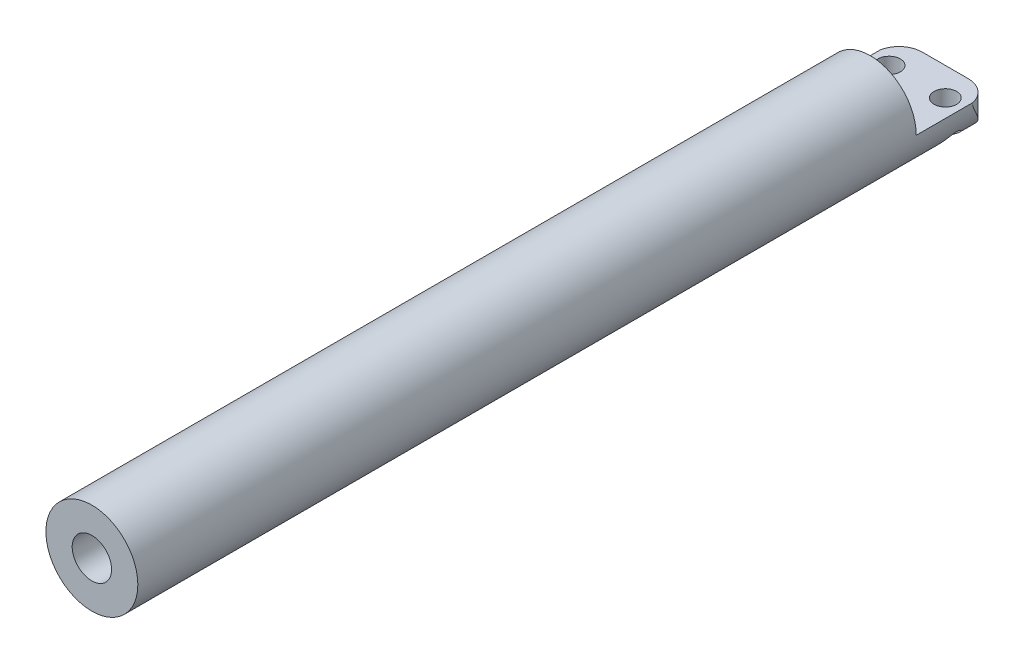
SolidWorks part; units mm, degrees
material "7050-T73510"
ref_plane "Plano frontal" through (0, 0, 0) normal (0, 0, 1) x (1, 0, 0)
ref_plane "Plano superior" through (0, 0, 0) normal (0, 1, 0) x (1, 0, 0)
ref_plane "Plano direito" through (0, 0, 0) normal (1, 0, 0) x (0, 0, -1)
sketch "Esboço1" plane through (0, 0, 0) normal (0, 0, 1) x (1, 0, 0)
  circle A0 centre (0, 0) radius 4.9
  dimension "D1" = 9.8
extrude "Ressalto-extrusão1" add sketch "Esboço1" along normal blind 91
sketch "Esboço10" plane through (0, 0, 0) normal (0, 0, -1) x (-1, 0, 0)
  line L0 (-5, 0) -> (5, 0)
  arc A0 (5, 0) -> (-5, 0) centre (0, 0) ccw
  dimension "D1" = 10
hole_wizard "Furo roscado de M51" positions "3DSketch6" profile "Esboço11" tap size "M5" standard "ISO"
sketch3d "3DSketch6"
  line L0 (0, 0, 91) -> (0, 0, 0) construction
  point P0 (0, 0, 91)
cosmetic thread "Rosca de furo1" parameters "D1"=10, "D2"=5
sketch "Esboço11" plane through (0, 0, 91) normal (1, 0, 0) x (0, -1, 0)
  line L0 (0, 0) -> (0, 14)
  line L1 (0, 14) -> (2.1, 12.7382)
  line L2 (2.1, 12.7382) -> (2.1, 0)
  line L5 (2.1, 0) -> (0, 0)
  line L10 (0, 14) -> (-2.1, 12.7382) construction
  line L11 (0, -6.35) -> (0, 107.95) construction
  dimension "Tap Drill Dia." = 4.2
  dimension "Tap Drill Depth" = 14
  dimension "Drill Angle" = 118
sketch "Esboço12" plane through (0, 0, 91) normal (0, 0, 1) x (1, 0, 0)
  point P0 (0, 0)
sketch "Esboço16" plane through (0, 0, 91) normal (0, 0, 1) x (1, 0, 0)
  circle A0 centre (0, 0) radius 5.1
  circle A1 centre (0, 0) radius 4.9
  circle A2 centre (0, 0) radius 4.9 construction
  dimension "D1" = 10.2
extrude "Corte-extrusão1" cut sketch "Esboço10" against normal blind 8
sketch "Esboço18" plane through (0, 0, 0) normal (0, 1, 0) x (1, 0, 0)
  line L0 (-4.9, 0) -> (0, -5) construction
  line L1 (0, -5) -> (0, 0) construction
  line L2 (0, 0) -> (-4.9, 0) construction
  line L3 (4.9, 0) -> (0, -5) construction
  line L4 (-4.9, -8) -> (-4.9, 0) construction
  line L5 (4.9, 0) -> (-4.9, 0) construction
  line L7 (-4.9, -2.0025) -> (-4.9, 0)
  line L8 (-4.9, 0) -> (-2.45, 0)
  line L9 (2.45, 0) -> (4.9, 0)
  line L10 (4.9, 0) -> (4.9, -2.0025)
  line L12 (-4.9, 0) -> (4.9, 0) construction
  line L14 (4.9, 0) -> (4.9, -8) construction
  arc A0 (-4.9, -2.0025) -> (-2.45, 0) centre (-2.45, -2.5) cw
  arc A1 (2.45, 0) -> (4.9, -2.0025) centre (2.45, -2.5) cw
  point P12 (4.4506, -0.8738)
  point P13 (2.3093, 0)
  point P23 (4.8, -1.8)
  dimension "D2" = 2.5
  dimension "D3" = 2.5
  dimension "D1" = 5
extrude "Corte-extrusão2" cut sketch "Esboço18" against normal through all
sketch "Esboço19" plane through (0, 0, 0) normal (0, 1, 0) x (1, 0, 0)
  line L0 (0, 0) -> (0, -3) construction
  line L1 (2.45, 0) -> (-2.45, 0) construction
  line L2 (-3, -3) -> (3, -3)
  point P7 (0, -3)
  dimension "D1" = 6
  dimension "D2" = 3
hole_wizard "Furo com folga de M21" positions "3DSketch7" profile "Esboço20" hole size "M2" standard "Ansi Metric" end condition through all
sketch3d "3DSketch7"
  point P0 (-3, 0, 3)
  point P3 (3, 0, 3)
sketch "Esboço20" plane through (-3, 0, 3) normal (1, 0, 0) x (0, 0, 1)
  line L0 (0, 0) -> (0, 4.9)
  line L1 (0, 4.9) -> (1.2, 4.9)
  line L2 (1.2, 4.9) -> (1.2, 0)
  line L5 (1.2, 0) -> (0, 0)
  line L11 (0, -6.35) -> (0, 107.95) construction
  dimension "Thru Hole Dia." = 2.4
  dimension "Thru Hole Depth" = 4.9
